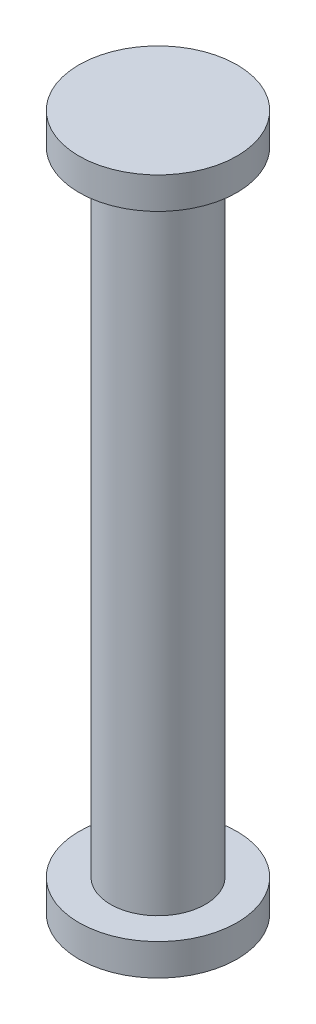
SolidWorks part; units mm, degrees
ref_plane "Front Plane" through (0, 0, 0) normal (0, 0, 1) x (1, 0, 0)
ref_plane "Top Plane" through (0, 0, 0) normal (0, 1, 0) x (1, 0, 0)
ref_plane "Right Plane" through (0, 0, 0) normal (1, 0, 0) x (0, 0, -1)
sketch "Sketch2" plane through (0, 0, 0) normal (0, 1, 0) x (1, 0, 0)
  circle A0 centre (0, 0) radius 7.5
  dimension "D1" = 15
extrude "Boss-Extrude1" add sketch "Sketch2" along normal blind 100
sketch "Sketch3" plane through (0, 100, 0) normal (0, 1, 0) x (1, 0, 0)
  circle A0 centre (0, 0) radius 12.5
  dimension "D1" = 25
extrude "Boss-Extrude2" add sketch "Sketch3" along normal blind 5
sketch "Sketch4" plane through (0, 0, 0) normal (0, -1, 0) x (1, 0, 0)
  circle A0 centre (0, 0) radius 12.5
extrude "Boss-Extrude3" add sketch "Sketch4" along normal blind 5
scale "Scale1" scale about centroid uniform scaling yes scale factor 0.5
